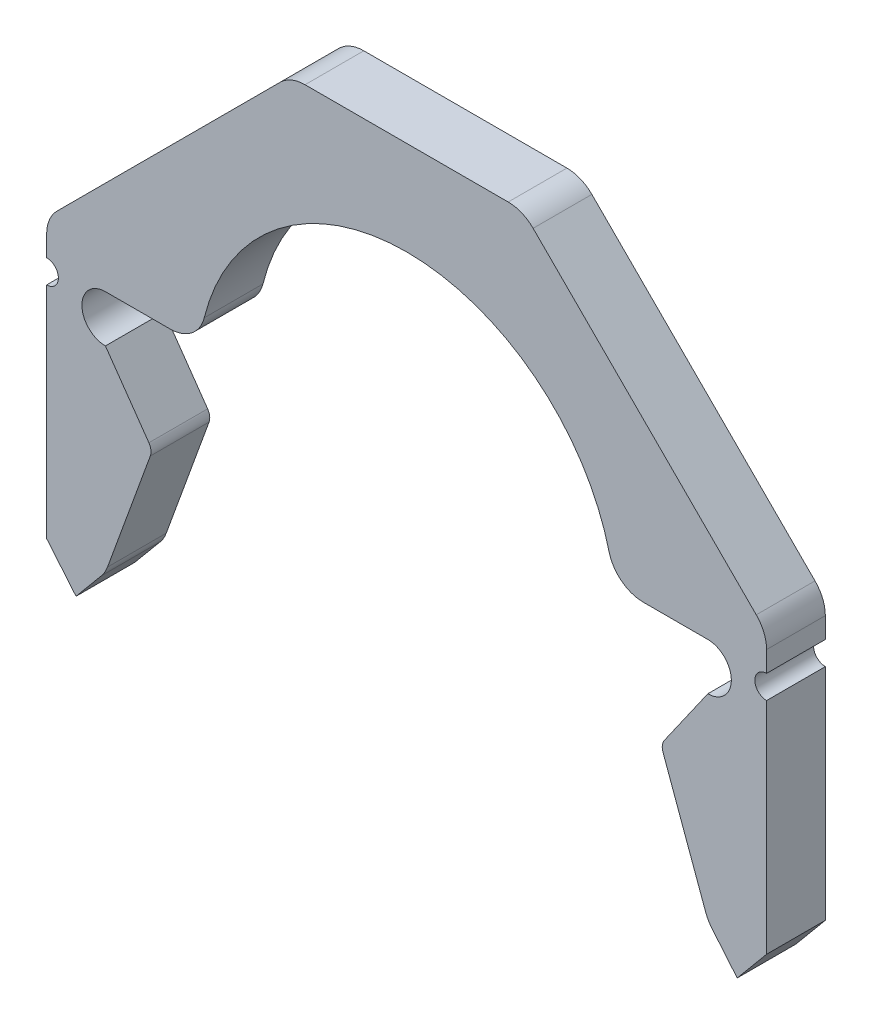
SolidWorks part; units mm, degrees
ref_plane "Front Plane" through (0, 0, 0) normal (0, 0, 1) x (1, 0, 0)
ref_plane "Top Plane" through (0, 0, 0) normal (0, 1, 0) x (1, 0, 0)
ref_plane "Right Plane" through (0, 0, 0) normal (1, 0, 0) x (0, 0, -1)
sketch "Sketch1" plane through (0, 0, 0) normal (0, 0, 1) x (1, 0, 0)
  line L0 (25.637, 2) -> (17.637, 2)
  line L1 (0, 0) -> (0, 25.75) construction
  line L2 (25.637, 2) -> (25.637, 10)
  line L3 (25.637, 10) -> (9.887, 25.75)
  line L4 (9.887, 25.75) -> (-9.887, 25.75)
  line L5 (-25.637, 10) -> (-9.887, 25.75)
  line L6 (-25.637, 2) -> (-25.637, 10)
  line L7 (-25.637, 2) -> (-17.637, 2)
  line L8 (-25.637, -2) -> (25.637, -2) construction
  line L9 (25.637, -2) -> (21.637, -7.7126)
  line L10 (21.637, -7.7126) -> (25.637, -18.7025)
  line L11 (25.637, -18.7025) -> (25.637, -2)
  line L12 (25.637, -18.7025) -> (28.137, -21.7025)
  line L13 (28.137, -21.7025) -> (30.637, -18.7025)
  line L15 (30.637, 5) -> (25.637, 10)
  line L17 (30.637, 5) -> (30.637, 2)
  line L18 (30.637, 0) -> (30.637, -18.7025)
  line L19 (-30.637, 0) -> (-30.637, -18.7025)
  line L20 (-30.637, 5) -> (-30.637, 2)
  line L21 (-30.637, 5) -> (-25.637, 10)
  line L22 (-28.137, -21.7025) -> (-30.637, -18.7025)
  line L23 (-25.637, -18.7025) -> (-28.137, -21.7025)
  line L24 (-25.637, -18.7025) -> (-25.637, -2)
  line L25 (-21.637, -7.7126) -> (-25.637, -18.7025)
  line L26 (-25.637, -2) -> (-21.637, -7.7126)
  circle A0 centre (0, 0) radius 16.75 construction
  arc A1 (17.637, 2) -> (-17.637, 2) centre (0, 0) ccw
  arc A3 (30.637, 2) -> (30.637, 0) centre (30.637, 1) ccw
  arc A4 (-30.637, 2) -> (-30.637, 0) centre (-30.637, 1) cw
  arc A5 (25.637, 2) -> (25.637, -2) centre (25.637, 0) cw
  arc A6 (-25.637, 2) -> (-25.637, -2) centre (-25.637, 0) ccw
  point P10 (0, 17.75)
  dimension "D1" = 33.5
  dimension "D2" = 1
  dimension "D14" = 5
  dimension "D3" = 8
  dimension "D4" = 8
  dimension "D5" = 2
  dimension "D6" = 8
  dimension "D7" = 45
  dimension "D9" = 55
  dimension "D10" = 20
  dimension "D11" = 4
  dimension "D12" = 2
  dimension "D13" = 2
  dimension "D15" = 3
extrude "Boss-Extrude1" add sketch "Sketch1" along normal mid plane 5
fillet "Fillet1" radius 3 8 edges at (25.637, -18.7025, 0) (-25.637, -18.7025, 0) (-30.637, 5, 0) (30.637, 5, 0) (-9.887, 25.75, 0) (9.887, 25.75, 0) (17.637, 2, 0) (-17.637, 2, 0)
fillet "Fillet2" radius 1 2 edges at (21.637, -7.7126, 0) (-21.637, -7.7126, 0)
